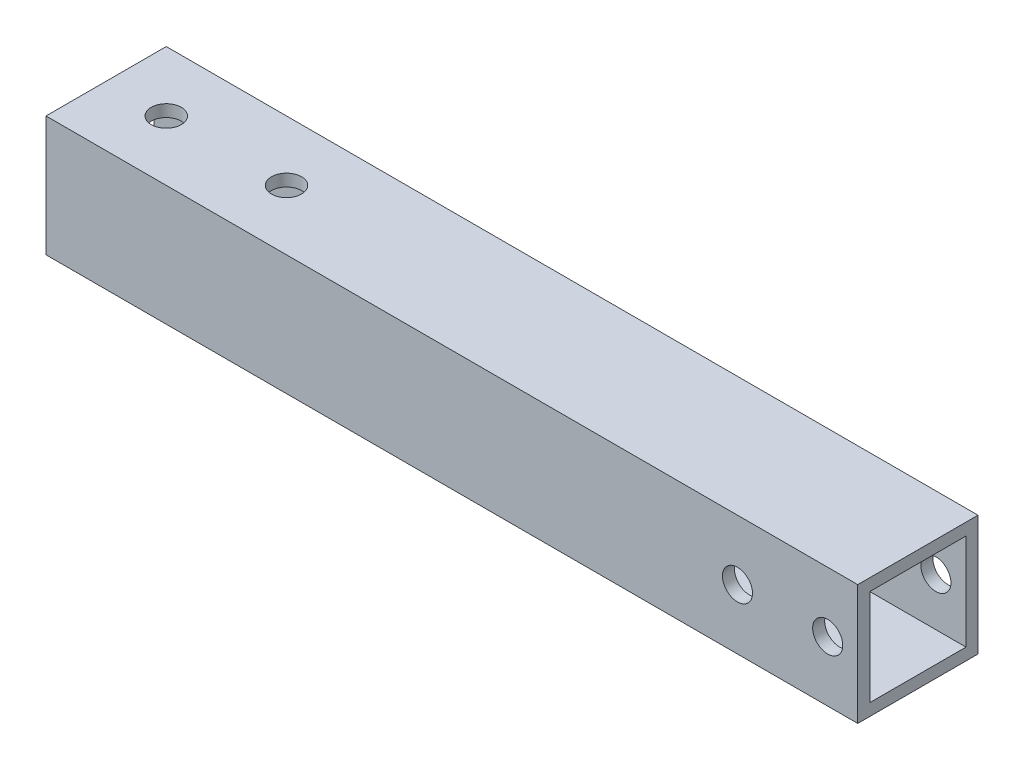
SolidWorks part; units mm, degrees
material "1345 Alloy"
ref_plane "Front Plane" through (0, 0, 0) normal (0, 0, 1) x (1, 0, 0)
ref_plane "Top Plane" through (0, 0, 0) normal (0, 1, 0) x (1, 0, 0)
ref_plane "Right Plane" through (0, 0, 0) normal (1, 0, 0) x (0, 0, -1)
sketch "Sketch1" plane through (0, 0, 0) normal (1, 0, 0) x (0, 0, -1)
  line L1 (-10, 10) -> (10, 10)
  line L2 (-10, 10) -> (-10, -10)
  line L3 (-10, -10) -> (10, -10)
  line L4 (10, 10) -> (10, -10)
  line L5 (-10, 10) -> (10, -10) construction
  line L6 (-10, -10) -> (10, 10) construction
  line L7 (-8, 8) -> (8, 8)
  line L8 (-8, 8) -> (-8, -8)
  line L9 (-8, -8) -> (8, -8)
  line L10 (8, 8) -> (8, -8)
  line L11 (-8, 8) -> (8, -8) construction
  line L12 (-8, -8) -> (8, 8) construction
  point P0 (0, 0)
  point P6 (0, 0)
  dimension "D1" = 20
  dimension "D2" = 20
  dimension "D3" = 16
extrude "Boss-Extrude1" add sketch "Sketch1" along normal blind 135
sketch "Sketch2" plane through (0, 0, 10) normal (0, 0, 1) x (1, 0, 0)
  line L0 (-5.0433, 0) -> (143.6048, 0) construction
  line L1 (135, 10) -> (135, -10) construction
  circle A0 centre (130, 0) radius 2.5
  circle A1 centre (115, 0) radius 2.5
  dimension "D1" = 5
  dimension "D2" = 5
  dimension "D3" = 15
  dimension "D4" = 5
extrude "Cut-Extrude1" cut sketch "Sketch2" against normal through all
sketch "Sketch3" plane through (0, 10, 0) normal (0, 1, 0) x (1, 0, 0)
  line L0 (-7.9487, 0) -> (139.5746, 0) construction
  line L1 (0, 10) -> (0, -10) construction
  circle A0 centre (10, 0) radius 2.5
  circle A1 centre (30, 0) radius 2.5
  dimension "D1" = 5
  dimension "D2" = 5
  dimension "D3" = 10
  dimension "D4" = 20
extrude "Cut-Extrude2" cut sketch "Sketch3" against normal through all
